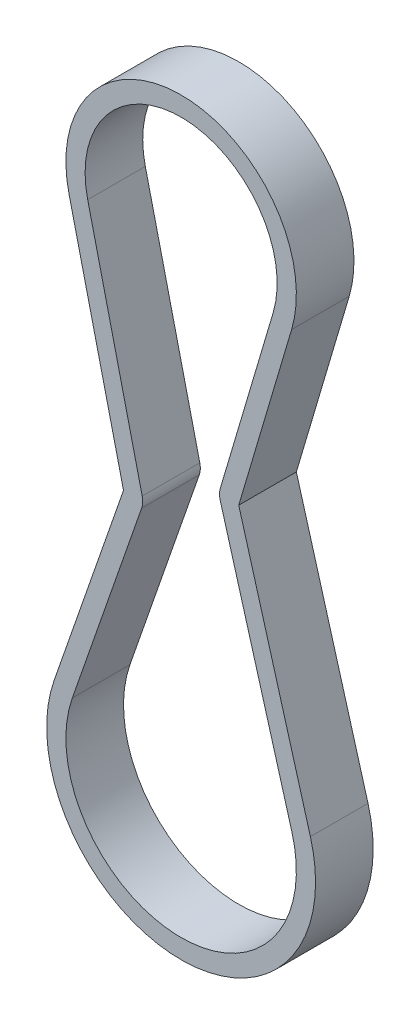
SolidWorks part; units mm, degrees
ref_plane "前视" through (0, 0, 0) normal (0, 0, 1) x (1, 0, 0)
ref_plane "上视" through (0, 0, 0) normal (0, 1, 0) x (1, 0, 0)
ref_plane "右视" through (0, 0, 0) normal (1, 0, 0) x (0, 0, -1)
sketch "草图1" plane through (0, 0, 0) normal (0, 0, 1) x (1, 0, 0)
  line L0 (0, 28.5388) -> (0, -49.4612) construction
  line L1 (0, 28.5388) -> (0, -4.4612) construction
  line L2 (0, -4.4612) -> (9, -4.4612) construction
  line L3 (0, 28.5388) -> (0, -11.4612) construction
  line L4 (0, -11.4612) -> (-9, -11.4612) construction
  line L5 (-14.594, 25.0724) -> (-6.0812, -10.7679)
  line L6 (-6.167, -12.4481) -> (-16.9981, -43.5397)
  line L7 (14.3826, 24.2795) -> (6.1235, -3.6094)
  line L8 (6.1151, -5.2842) -> (17.3094, -44.5231)
  line L9 (9, -4.4612) -> (20.1943, -43.7001)
  line L10 (-9, -11.4612) -> (-19.8311, -42.5528)
  line L11 (-17.5128, 24.3792) -> (-9, -11.4612)
  line L12 (17.2591, 23.4276) -> (9, -4.4612)
  arc A0 (14.3826, 24.2795) -> (-14.594, 25.0724) centre (0, 28.5388) ccw
  arc A1 (-16.9981, -43.5397) -> (17.3094, -44.5231) centre (0, -49.4612) ccw
  arc A2 (-6.167, -12.4481) -> (-6.0812, -10.7679) centre (-9, -11.4612) ccw
  arc A3 (6.1235, -3.6094) -> (6.1151, -5.2842) centre (9, -4.4612) ccw
  arc A4 (-19.8311, -42.5528) -> (20.1943, -43.7001) centre (0, -49.4612) ccw
  arc A5 (-9, -11.4612) -> (-9, -11.4612) centre (-9, -11.4612) ccw
  arc A6 (17.2591, 23.4276) -> (-17.5128, 24.3792) centre (0, 28.5388) ccw
  arc A7 (9, -4.4612) -> (9, -4.4612) centre (9, -4.4612) ccw
  dimension "D1" = 78
  dimension "D6" = 6
  dimension "D7" = 6
  dimension "D8" = 30
  dimension "D9" = 36
  dimension "D2" = 33
  dimension "D3" = 40
  dimension "D4" = 9
  dimension "D5" = 9
  dimension "D10" = 3
extrude "凸台-拉伸1" add sketch "草图1" along normal blind 9 contours A3 L7 A0 L5 A2 L6 A1 L8 | A6 L11 A5 L10 A4 L9 A7 L12
